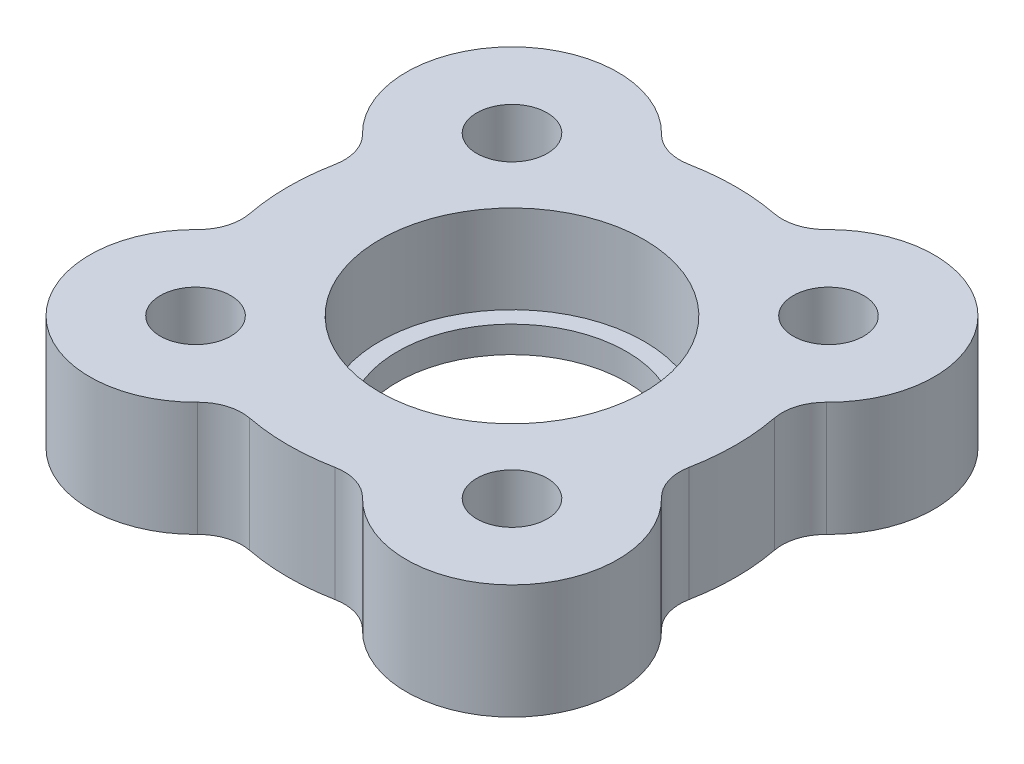
SolidWorks part; units mm, degrees
material "1060 Alloy"
ref_plane "Front" through (0, 0, 0) normal (0, 0, 1) x (1, 0, 0)
ref_plane "Top" through (0, 0, 0) normal (0, 1, 0) x (1, 0, 0)
ref_plane "Right" through (0, 0, 0) normal (1, 0, 0) x (0, 0, -1)
sketch "Sketch1" plane through (0, 0, 0) normal (0, 1, 0) x (1, 0, 0)
  circle A0 centre (-17.9605, 17.9605) radius 4
  circle A1 centre (17.9605, 17.9605) radius 4
  circle A2 centre (17.9605, -17.9605) radius 4
  circle A3 centre (-17.9605, -17.9605) radius 4
  circle A4 centre (0, 0) radius 13
  arc A5 (-9.3775, 26.347) -> (-26.347, 9.3775) centre (-17.9605, 17.9605) ccw
  arc A6 (26.347, 9.3775) -> (9.3775, 26.347) centre (17.9605, 17.9605) ccw
  arc A7 (9.3775, -26.347) -> (26.347, -9.3775) centre (17.9605, -17.9605) ccw
  arc A8 (-26.347, -9.3775) -> (-9.3775, -26.347) centre (-17.9605, -17.9605) ccw
  arc A9 (-24.9332, 4.8471) -> (-24.9332, -4.8471) centre (0, 0) ccw
  arc A10 (-4.8471, -24.9332) -> (4.8471, -24.9332) centre (0, 0) ccw
  arc A11 (24.9332, -4.8471) -> (24.9332, 4.8471) centre (0, 0) ccw
  arc A12 (-4.8471, 24.9332) -> (-9.3775, 26.347) centre (-5.8013, 29.8413) cw
  arc A13 (4.8471, 24.9332) -> (-4.8471, 24.9332) centre (0, 0) ccw
  arc A14 (9.3775, 26.347) -> (4.8471, 24.9332) centre (5.8013, 29.8413) cw
  arc A15 (26.347, 9.3775) -> (24.9332, 4.8471) centre (29.8413, 5.8013) ccw
  arc A16 (24.9332, -4.8471) -> (26.347, -9.3775) centre (29.8413, -5.8013) ccw
  arc A17 (9.3775, -26.347) -> (4.8471, -24.9332) centre (5.8013, -29.8413) ccw
  arc A18 (-4.8471, -24.9332) -> (-9.3775, -26.347) centre (-5.8013, -29.8413) ccw
  arc A19 (-24.9332, -4.8471) -> (-26.347, -9.3775) centre (-29.8413, -5.8013) cw
  arc A20 (-24.9332, 4.8471) -> (-26.347, 9.3775) centre (-29.8413, 5.8013) ccw
  point P0 (0, 0)
  point P17 (0, 0)
  point P27 (0, 0)
  dimension "D5" = 8
  dimension "D6" = 26
  dimension "D1" = 5
  dimension "D3" = 25.4
  dimension "D4" = 4
  dimension "D8" = 4
extrude "body and main holes" add sketch "Sketch1" along normal blind 13
sketch "Sketch3" plane through (0, 13, 0) normal (0, -1, 0) x (1, 0, 0)
  circle A0 centre (0, 0) radius 15
  dimension "D1" = 30
extrude "bearing hole" cut sketch "Sketch3" along normal blind 10
sketch "Sketch4" plane through (0, 13, 0) normal (0, 1, 0) x (1, 0, 0)
  line L0 (-17.9605, 17.9605) -> (17.9605, -17.9605) construction
sketch "Sketch5" plane through (0, 0, 0) normal (0, -1, 0) x (1, 0, 0)
  line L0 (-17.9605, -17.9605) -> (17.9605, 17.9605) construction
equation "\"D3@Sketch1\"=\"square plate bolt pattern diameter\"/2"
equation "\"D1@body and main holes\"=\"bearing plate thickness\""
equation "\"D1@Sketch3\" = \"bearing OD\""
equation "\"D1@bearing hole\"=\"bearing bore\""
equation "\"D5@Sketch1\"=\"square plate bolt hole ID\""
equation "\"D6@Sketch1\"=\"bearing plate bearing stop ID\""
equation "\"bearing OD\" = 30mm"
equation "\"bearing outer race thickness\"= 1mm"
equation "\"bearing ID\"= 10mm"
equation "\"bearing depth\"= 9mm"
equation "\"bearing inner race thickness\"= 1mm"
equation "\"bearing bore\" = \"bearing depth\" + 1mm"
equation "\"small seal OD\" = 20mm"
equation "\"small seal ID\"= 8mm"
equation "\"small seal depth\" = 8.3mm"
equation "\"small seal bore\" = \"small seal depth\" + 1mm"
equation "\"big seal OD\" = 27mm"
equation "\"big seal ID\"= 15mm"
equation "\"big seal depth\"= 8.3mm"
equation "\"big seal bore\" = \"big seal depth\" + 1mm"
equation "\"z\" = 8 \t\t\t\t'number of blades"
equation "\"de\" = 0.426in \t\t\t\t'entrance eye diameter"
equation "\"d2\" = 2.097in \t\t\t\t'outer diameter of the impeller "
equation "\"d_exit\" = 0.18in \t\t\t'volute throat aka D4"
equation "\"theta\" = 15"
equation "\"b2\" = .071in\t\t\t\t\t\t\t\t'tip height from disc surface at d2"
equation "\"b1\" = \"b2\" + (\"d2\"/2 - \"de\"/2)*sin(\"theta\")\t\t\t\t'tip height from disc surface at inlet eye"
equation "\"s\" = ( 1/\"z\")*(3.14*\"de\" - (3.14*(\"de\"^2) / (4*(\"b1\"))))\t\t'thickness of blades, calculated from area"
equation "\"s_opening\" = (3.14*\"de\" - \"z\"*\"s\")/\"z\"\t\t\t\t\t'ideal gap between blades, calculated from area"
equation "\"area_eye\"=3.14*(\"de\"^2)/4\t\t\t\t\t\t'eye area"
equation "\"single_channel_area\"=\"s_opening\"*\"b1\"\t\t\t\t\t'ideal area between two blades"
equation "\"bit size\"= 1mm"
equation "\"inlet area before cut\" = \"minimum channel width\" * (\"z\") * \"b1\"\t\t\t\t'if minimum channel width>s_opening, this is larger than area_eye"
equation "\"area to cut\" = \"inlet area before cut\" - \"area_eye\"\t\t\t\t\t\t'amount of extra area\t\t\t\t\t"
equation "\"height to cut\" = \"area to cut\" / ((\"z\")* \"minimum channel width\")+ .0001in\t\t\t'the 0.0001 in cut is to avoid errors in model"
equation "\"final impeller center height\" = \"impeller base thickness\" + \"b1\" - \"height to cut\"\t\t'corrected height so that sum of channel areas equals eye area"
equation "\"impeller upper clearance\"= .5mm"
equation "\"impeller horizontal clearance\"= (\"d2\"*1.15 - \"d2\")/2 \t\t\t\t\t'clearance based on D2-D3 ratio for circular volute, ranges 1.15 to 1.2"
equation "\"impeller bottom clearance\"= .5mm"
equation "\"impeller base thickness\"= 2mm"
equation "\"impeller boss depth\" = \"shaft impeller section length\" + 3mm + \"impeller bolt head depth\" - \"impeller base thickness\""
equation "\"impeller boss diameter\" = \"big seal ID\""
equation "\"impeller dowel diameter\" = 2mm"
equation "\"impeller bolt head diameter\" = 7.5mm"
equation "\"impeller bolt head depth\" = 4mm"
equation "\"impeller shaft bore\"= 8mm"
equation "\"impeller shaft bore depth\" = \"impeller boss depth\" + \"impeller base thickness\" - \"impeller bolt head depth\" - 3mm"
equation "\"impeller dowel length\" = 2mm*2 + \"impeller shaft bore\""
equation "\"impeller screw hole bore\" = 4mm"
equation "\"shaft impeller screw hole diameter\" = \"impeller screw hole bore\""
equation "\"shaft impeller section length\" = \"big seal plate thickness\"/2 + \"impeller bottom clearance\" + \"impeller base thickness\" - \"impeller bolt head depth\" - 3mm"
equation "\"shaft impeller screw hole depth\" = \"shaft impeller section length\"-\"impeller dowel diameter\"-2mm"
equation "\"shaft impeller section diameter\" = \"impeller shaft bore\""
equation "\"shaft seal section diameter\"=\"small seal ID\""
equation "\"shaft seal section length\"= \"big seal plate thickness\"/2 + \"small seal bore\" + 2mm"
equation "\"shaft bearing section diameter\" = \"bearing ID\""
equation "\"shaft bearing section length\" = \"bearing bore\""
equation "\"shaft bearing stop diameter\" = \"bearing ID\" + 2mm"
equation "\"shaft bearing stop length\" = 2mm"
equation "\"shaft coupler section diameter\" = 8mm"
equation "\"shaft coupler section length\" = \"shaft bearing stop length\" + \"coupler length\"/2 + 4mm"
equation "\"coupler motor shaft hole ID\"= 8mm"
equation "\"coupler OD\"= 17mm"
equation "\"coupler length\"= 25mm"
equation "\"square plate diameter\" = 3in"
equation "\"square plate bolt pattern diameter\"= 2in"
equation "\"square plate bolt hole ID\" = 8mm"
equation "\"bearing plate bearing stop ID\" = \"bearing OD\" - 4mm"
equation "\"bearing plate bearing stop depth\" = 3mm"
equation "\"bearing plate thickness\" = \"bearing bore\" + \"bearing plate bearing stop depth\""
equation "\"small seal plate lip depth\" = \"shaft bearing stop length\" + 1mm"
equation "\"small seal plate lip ID\" = \"small seal OD\" - 3mm"
equation "\"small seal plate thickness\" = \"small seal plate lip depth\" + \"small seal bore\""
equation "\"big seal plate lip depth\" = 8mm"
equation "\"big seal plate thickness\" = \"big seal plate outer thickness\" + \"big seal plate riser height\""
equation "\"big seal plate pressure hole diameter\" = .125in\t\t\t'this is 1/8 drill "
equation "\"big seal plate pressure tap diameter\" = .328125in \t\t'this is 21/64 drill for a 1/8 ANPT tap"
equation "\"big seal plate pressure tap depth\" = 9mm"
equation "\"impeller cavity center height\"= \"impeller bottom clearance\" + \"impeller upper clearance\" + \"final impeller center height\""
equation "\"impeller cavity diameter\"= 2 * \"impeller horizontal clearance\" + \"d2\" \t\t\t'called D3 analytically"
equation "\"impeller cavity outer height\"= \"impeller bottom clearance\" + \"impeller upper clearance\" + \"impeller base thickness\" + \"b2\" \t\t\t'this is height at impeller diameter d2, not at d3"
equation "\"impeller housing bolt count\" = 8"
equation "\"impeller housing bolt diameter\" = 6mm"
equation "\"impeller housing bolt pattern diameter\" = 3in"
equation "\"impeller housing o-ring channel height\"= 1.5mm"
equation "\"impeller housing o ring channel width\"= 1.5mm"
equation "\"impeller housing o-ring diameter\" = 2in"
equation "\"impeller housing threaded inlet diameter\" = 0.6875in \t\t\t'this is the 11/16 drill size for 1/2 npt fitting"
equation "\"impeller housing threaded inlet depth\"= 20mm"
equation "\"impeller housing thickness\"= \"impeller housing exit threaded diameter\" + 2*\"impeller housing outlet purchase\""
equation "\"impeller housing exit threaded diameter\"= 0.6875in \t\t\t'this is the 11/16 drill size for 1/2 npt fitting"
equation "\"impeller housing exit threaded depth\"= 12mm"
equation "\"impeller housing diameter\" = 4in"
equation "\"impeller housing diffuser conical angle\"=10"
equation "\"impeller housing diffuser tangent angle\"=0"
equation "\"impeller housing outlet purchase\" = 6mm"
equation "\"motor to housing distance\" = \"motor shaft pride\" + \"shaft coupler section length\" - \"bearing plate bearing stop depth\" + 2mm"
equation "\"motor mount coupler hole diameter\"= \"coupler OD\"+ 4mm"
equation "\"motor mount to housing post radius\"= ( 3 * \"square plate bolt hole ID\" ) / 2"
equation "\"motor mount m4 screw hole diameter\"= 4mm"
equation "\"motor mount m4 head diameter\"= 7.25mm"
equation "\"motor mount m4 head depth\"= 4mm"
equation "\"motor mount m4 pattern diamater\" = 30mm"
equation "\"motor mount plate thickness\"= 8mm + \"motor mount m4 head depth\""
equation "\"motor shaft pride\"= 32mm"
equation "\"motor shaft flat section length from tip\"= 25.7mm"
equation "\"motor shaft bore end clearance\"= 2mm"
equation "\"coupler shaft to motor clearance\" = 2mm"
equation "\"motor mount shaft hole depth\"= \"motor shaft pride\""
